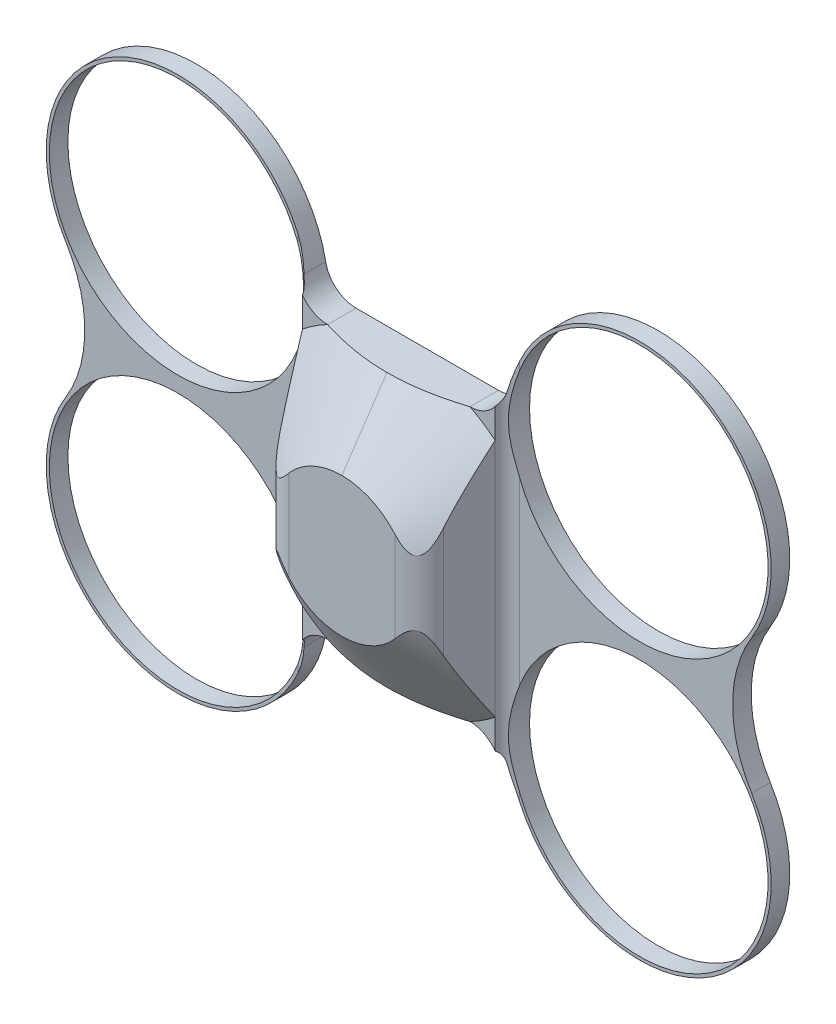
SolidWorks part; units mm, degrees
ref_plane "Front Plane" through (0, 0, 0) normal (0, 0, 1) x (1, 0, 0)
ref_plane "Top Plane" through (0, 0, 0) normal (0, 1, 0) x (1, 0, 0)
ref_plane "Right Plane" through (0, 0, 0) normal (1, 0, 0) x (0, 0, -1)
sketch "Sketch1" plane through (0, 0, 0) normal (0, 0, 1) x (1, 0, 0)
  line L0 (0, 0) -> (0, 31.402) construction
  line L1 (0, 0) -> (-57.7561, 0) construction
  line L2 (22.9612, 44) -> (-22.9612, 44)
  line L3 (22.9612, -44) -> (-22.9612, -44)
  arc A0 (110.703, 21.7381) -> (32.7781, 52.0952) centre (74.5, 44) ccw
  arc A1 (-110.703, 21.7381) -> (-32.7781, 52.0952) centre (-74.5, 44) cw
  arc A2 (110.703, -21.7381) -> (32.7781, -52.0952) centre (74.5, -44) cw
  arc A3 (-110.703, -21.7381) -> (-32.7781, -52.0952) centre (-74.5, -44) ccw
  arc A4 (110.703, 21.7381) -> (110.703, -21.7381) centre (146.0542, 0) ccw
  arc A5 (22.9612, 44) -> (32.7781, 52.0952) centre (22.9612, 54) ccw
  arc A6 (-22.9612, 44) -> (-32.7781, 52.0952) centre (-22.9612, 54) cw
  arc A7 (-110.703, 21.7381) -> (-110.703, -21.7381) centre (-146.0542, 0) cw
  arc A8 (22.9612, -44) -> (32.7781, -52.0952) centre (22.9612, -54) cw
  arc A9 (-22.9612, -44) -> (-32.7781, -52.0952) centre (-22.9612, -54) ccw
  point P23 (0, 44)
  dimension "D1" = 85
  dimension "D2" = 173
  dimension "D3" = 234
  dimension "D4" = 83
  dimension "D5" = 44
  dimension "D6" = 20
extrude "Boss-Extrude1" add sketch "Sketch1" along normal blind 27.56
sketch "Sketch2" plane through (0, 0, 0) normal (0, 1, 0) x (1, 0, 0)
  line L0 (117, -6) -> (35.7676, -6)
  line L1 (117, -27.56) -> (117, 0) construction
  line L2 (31.1085, -9.1854) -> (26.4332, -21.1893)
  line L3 (22.9612, -27.56) -> (32.7781, -27.56) construction
  line L9 (0, -1013.78) -> (0, 48986.22) construction
  line L10 (17.115, -27.56) -> (117, -27.56)
  line L11 (117, -27.56) -> (117, -6)
  line L12 (117, 0) -> (32.7781, 0) construction
  line L13 (-117, -27.56) -> (-117, -6)
  line L14 (-17.115, -27.56) -> (-117, -27.56)
  line L15 (-31.1085, -9.1854) -> (-26.4332, -21.1893)
  line L16 (-117, -6) -> (-35.7676, -6)
  arc A0 (26.4332, -21.1893) -> (17.115, -27.56) centre (17.115, -17.56) cw
  arc A1 (35.7676, -6) -> (31.1085, -9.1854) centre (35.7676, -11) ccw
  arc A2 (-35.7676, -6) -> (-31.1085, -9.1854) centre (-35.7676, -11) cw
  arc A3 (-26.4332, -21.1893) -> (-17.115, -27.56) centre (-17.115, -17.56) ccw
  point P20 (23.9519, -27.56)
  point P29 (-23.9519, -27.56)
  dimension "D3" = 10
  dimension "D4" = 5
  dimension "D1" = 17.115
  dimension "D2" = 111.28
  dimension "D5" = 6
extrude "Cut-Extrude1" cut sketch "Sketch2" against normal through all both and the other way through all
sketch "Sketch3" plane through (0, 0, 0) normal (0, 0, -1) x (-1, 0, 0)
  line L0 (-1000, 0) -> (49000, 0) construction
  line L1 (0, 44.759) -> (0, 50044.759) construction
  circle A0 centre (74.5, 44) radius 41.5
  arc A1 (110.703, 21.7381) -> (32.7781, 52.0952) centre (74.5, 44) ccw construction
  circle A2 centre (-74.5, 44) radius 41.5
  circle A3 centre (-74.5, 44) radius 41.5
  circle A4 centre (74.5, 44) radius 41.5
  circle A5 centre (74.5, -44) radius 41.5
  circle A6 centre (-74.5, -44) radius 41.5
  dimension "D1" = 1
extrude "Cut-Extrude2" cut sketch "Sketch3" against normal through all both contours A2 | A6 | A0 | A5
sketch "Sketch4" plane through (0, 0, 27.56) normal (0, 0, 1) x (1, 0, 0)
  circle A0 centre (0, 0) radius 22.5
  dimension "D1" = 45
sketch "Sketch5" plane through (0, 0, 0) normal (1, 0, 0) x (0, 0, -1)
  line L0 (-27.56, 22.5) -> (-9.1854, 49.6392)
  line L1 (-27.56, 44) -> (-27.56, -44) construction
  line L3 (-27.56, 48.2016) -> (-27.56, 22.5)
  line L4 (-27.56, 22.5) -> (-27.56, -22.5) construction
  line L5 (-9.1854, 49.6392) -> (-9.1854, 86.5)
  line L6 (-9.1854, 86.5) -> (-27.56, 86.5)
  line L7 (-27.56, 86.5) -> (-27.56, 48.2016)
  line L8 (0, 86.5) -> (-6, 86.5) construction
  dimension "D1" = 34.1
sweep "Cut-Sweep1" cut profiles "Sketch5" path "Sketch4"
